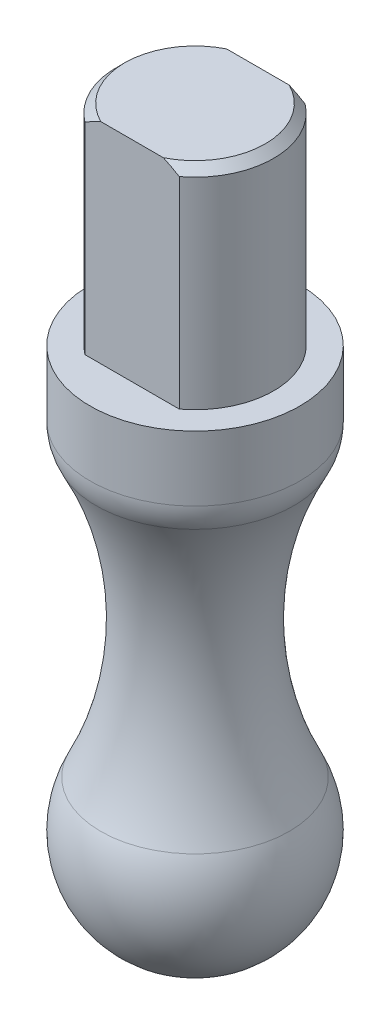
SolidWorks part; units mm, degrees
ref_plane "Front" through (0, 0, 0) normal (0, 0, 1) x (1, 0, 0)
ref_plane "Top" through (0, 0, 0) normal (0, 1, 0) x (1, 0, 0)
ref_plane "Right" through (0, 0, 0) normal (1, 0, 0) x (0, 0, -1)
sketch "Sketch1" plane through (0, 0, 0) normal (0, 0, 1) x (1, 0, 0)
  line L0 (0, 0) -> (0, 18.5003) construction
  line L2 (9.525, 0) -> (0, 0)
  line L3 (0, 0) -> (0, -88.9)
  line L4 (9.525, 0) -> (9.525, -25.4)
  line L5 (9.525, -25.4) -> (12.7, -25.4)
  line L7 (12.7, -25.4) -> (12.7, -33.2644)
  line L8 (0, -88.9) -> (-12.8341, -88.9)
  arc A0 (11.9686, -36.223) -> (11.4201, -70.6438) centre (45.6803, -53.975) ccw
  arc A1 (11.4201, -70.6438) -> (0, -88.9) centre (0, -76.2) cw
  arc A2 (12.7, -33.2644) -> (11.9686, -36.223) centre (6.35, -33.2644) cw
  dimension "D1" = 38.1
  dimension "D2" = 12.7
  dimension "D6" = 6.35
  dimension "D3" = 25.4
  dimension "D4" = 88.9
  dimension "D5" = 53.975
  dimension "D7" = 19.05
  dimension "D8" = 25.4
revolve "Revolve1" add sketch "Sketch1" angle 360 about L0
chamfer "Chamfer1" distance 1.016 angle 45 1 edges at (0, 0, -9.525)
sketch "Sketch2" plane through (0, 0, 0) normal (0, 1, 0) x (-1, 0, 0)
  line L0 (0, 0) -> (-12.7, 0) construction
  line L1 (-5.715, 7.62) -> (5.715, 7.62)
  line L2 (-5.715, -7.62) -> (5.715, -7.62)
  circle A0 centre (0, 0) radius 12.7 construction
  arc A3 (5.715, 7.62) -> (-5.715, 7.62) centre (0, 0) ccw
  circle A4 centre (0, 0) radius 9.525 construction
  arc A5 (-5.715, -7.62) -> (5.715, -7.62) centre (0, 0) ccw
  dimension "D1" = 7.62
extrude "Cut-Extrude1" cut sketch "Sketch2" against normal up to surface (25.4 mm away) up to face at (0, -25.4, -12.7)
